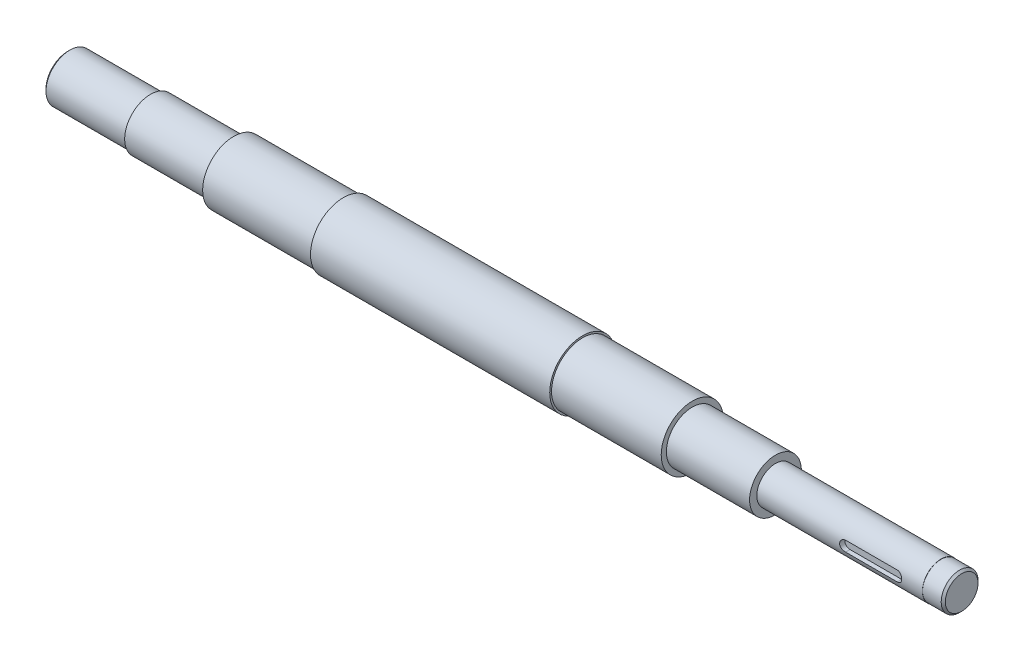
SolidWorks part; units mm, degrees
material "AISI 304"
ref_plane "前基準面" through (0, 0, 0) normal (0, 0, 1) x (1, 0, 0)
ref_plane "上基準面" through (0, 0, 0) normal (0, 1, 0) x (1, 0, 0)
ref_plane "右基準面" through (0, 0, 0) normal (1, 0, 0) x (0, 0, -1)
sketch "草圖1" plane through (0, 0, 0) normal (0, 0, 1) x (1, 0, 0)
  line L39 (0, 0) -> (50000, 0) construction
  line L40 (0, 0) -> (0, 15.875) construction
  line L41 (57.8, 15.875) -> (-57.8, 15.875)
  line L42 (-57.8, 15.875) -> (-57.8, 15)
  line L43 (-57.8, 15) -> (-110.8, 15)
  line L44 (-110.8, 15) -> (-110.8, 12.5)
  line L45 (-110.8, 12.5) -> (-151, 12.5)
  line L46 (-151, 12.5) -> (-151, 11.5)
  line L47 (-151, 11.5) -> (-190, 11.5)
  line L48 (-191, 10.5) -> (-191, 0)
  line L49 (110.8, 12.5) -> (151, 12.5)
  line L50 (110.8, 15) -> (110.8, 12.5)
  line L51 (57.8, 15) -> (110.8, 15)
  line L52 (57.8, 15.875) -> (57.8, 15)
  line L53 (151, 12.5) -> (151, 9)
  line L54 (151, 9) -> (231, 9)
  line L55 (231, 9) -> (231, 8.9)
  line L56 (231, 8.9) -> (240, 8.9)
  line L57 (241, 7.9) -> (241, 0)
  line L58 (241, 0) -> (-191, 0)
  line L59 (-190, 11.5) -> (-191, 10.5)
  line L60 (240, 8.9) -> (241, 7.9)
  point P11 (-191, 11.5)
  point P22 (241, 8.9)
  dimension "D1" = 40
  dimension "D2" = 53
  dimension "D5" = 115.6
  dimension "D6" = 10
  dimension "D7" = 90
  dimension "D8" = 432
  dimension "D9" = 23
  dimension "D10" = 25
  dimension "D11" = 30
  dimension "D12" = 31.75
  dimension "D13" = 18
  dimension "D14" = 17.8
revolve "旋轉1" add sketch "草圖1" angle 360 about L39
sketch "草圖2" plane through (0, 0, 0) normal (0, 0, 1) x (1, 0, 0)
  line L0 (193.5, 0) -> (218.5, 0) construction
  line L1 (193.5, 2.5) -> (218.5, 2.5)
  line L2 (193.5, -2.5) -> (218.5, -2.5)
  line L4 (231, -9) -> (231, 9) construction
  arc A0 (193.5, 2.5) -> (193.5, -2.5) centre (193.5, 0) ccw
  arc A1 (218.5, -2.5) -> (218.5, 2.5) centre (218.5, 0) ccw
  point P3 (206, 0)
  point P10 (191, 0)
  point P11 (221, 0)
  dimension "D2" = 30
  dimension "D3" = 10
  dimension "D1" = 5
extrude "除料-伸長1" cut sketch "草圖2" against normal blind 2.5 from offset 9
